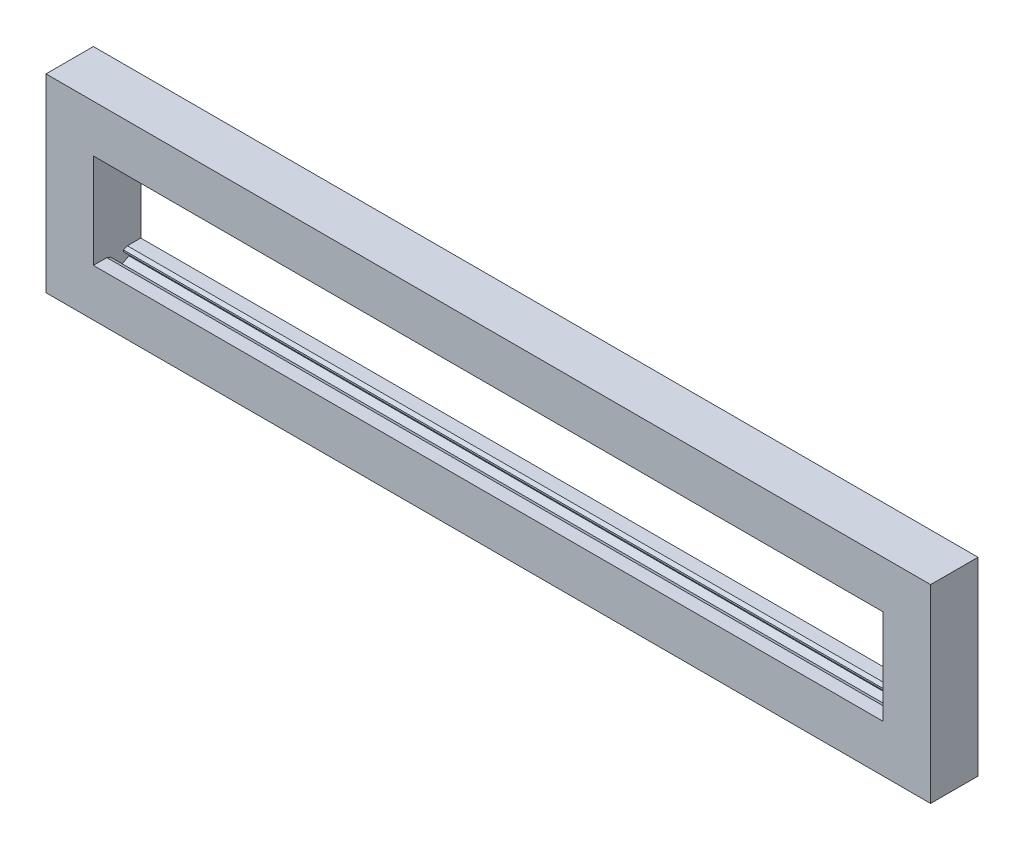
SolidWorks part; units mm, degrees
material "6061-T6 (SS)"
ref_plane "Front Plane" through (0, 0, 0) normal (0, 0, 1) x (1, 0, 0)
ref_plane "Top Plane" through (0, 0, 0) normal (0, 1, 0) x (1, 0, 0)
ref_plane "Right Plane" through (0, 0, 0) normal (1, 0, 0) x (0, 0, -1)
sketch "Sketch1" plane through (0, 0, 0) normal (0, 0, 1) x (1, 0, 0)
  line L0 (-280, 60) -> (280, 60)
  line L1 (-250, -30) -> (250, -30)
  line L2 (-250, -30) -> (-250, 30)
  line L3 (-250, 30) -> (250, 30)
  line L4 (250, -30) -> (250, 30)
  line L5 (-250, -30) -> (250, 30) construction
  line L6 (-250, 30) -> (250, -30) construction
  line L7 (280, -60) -> (280, 60)
  line L8 (-280, -60) -> (280, -60)
  line L9 (-280, -60) -> (-280, 60)
  point P0 (0, 0)
  dimension "D1" = 500
  dimension "D2" = 60
  dimension "D3" = 30
extrude "Boss-Extrude1" add sketch "Sketch1" along normal mid plane 30
sketch "Sketch2" plane through (0, 0, 0) normal (1, 0, 0) x (0, 0, -1)
  line L0 (-4, 31) -> (-6.5, 30)
  line L1 (-15, 30) -> (15, 30) construction
  line L2 (-4, 31) -> (-4, 32)
  line L3 (-4, 32) -> (-7.5, 32)
  line L4 (-7.5, 36) -> (-7.5, 32)
  line L5 (-7.5, 36) -> (0, 40)
  line L6 (0, 40) -> (7.5, 36)
  line L7 (7.5, 36) -> (7.5, 32)
  line L8 (7.5, 32) -> (4, 32)
  line L9 (4, 32) -> (4, 31)
  line L10 (4, 31) -> (6.5, 30)
  line L11 (0, 40) -> (0, 30) construction
  line L12 (0, 0) -> (-53.2537, 0) construction
  line L13 (-6.5, 30) -> (6.5, 30)
  line L14 (0, -40) -> (0, -30) construction
  line L15 (-6.5, -30) -> (6.5, -30)
  line L16 (4, -31) -> (6.5, -30)
  line L17 (4, -32) -> (4, -31)
  line L18 (7.5, -32) -> (4, -32)
  line L19 (7.5, -36) -> (7.5, -32)
  line L20 (0, -40) -> (7.5, -36)
  line L21 (-7.5, -36) -> (0, -40)
  line L22 (-7.5, -36) -> (-7.5, -32)
  line L23 (-4, -32) -> (-7.5, -32)
  line L24 (-4, -31) -> (-4, -32)
  line L25 (-4, -31) -> (-6.5, -30)
  dimension "D1" = 8
  dimension "D2" = 1
  dimension "D3" = 1
  dimension "D4" = 4
  dimension "D5" = 10
  dimension "D6" = 13
  dimension "D7" = 15
extrude "Cut-Extrude1" cut sketch "Sketch2" against normal mid plane 500
ref_point "Point1"
